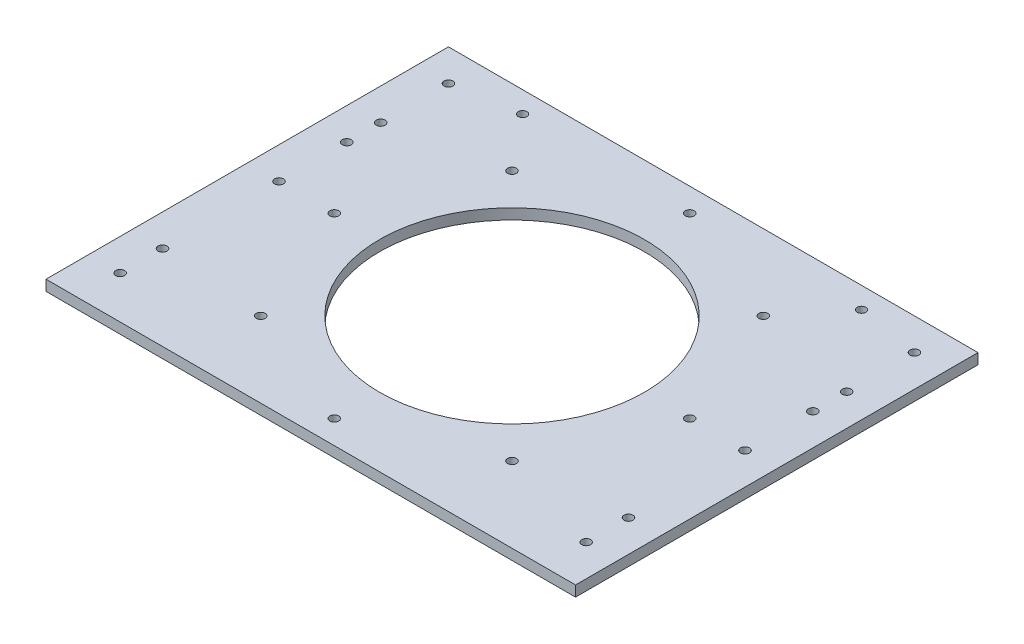
SolidWorks part; units mm, degrees
material "Thornel Mat VMA"
ref_plane "前视基准面" through (0, 0, 0) normal (0, 0, 1) x (1, 0, 0)
ref_plane "上视基准面" through (0, 0, 0) normal (0, 1, 0) x (1, 0, 0)
ref_plane "右视基准面" through (0, 0, 0) normal (1, 0, 0) x (0, 0, -1)
other "Configuration Table"
sketch "草图1" plane through (0, 0, 0) normal (0, 1, 0) x (1, 0, 0)
  line L1 (-125, 95) -> (125, 95)
  line L2 (-125, 95) -> (-125, -95)
  line L3 (-125, -95) -> (125, -95)
  line L4 (125, 95) -> (125, -95)
  line L5 (-125, 95) -> (125, -95) construction
  line L6 (-125, -95) -> (125, 95) construction
  point P0 (0, 0)
  dimension "D1" = 250
  dimension "D2" = 190
extrude "凸台-拉伸1" add sketch "草图1" along normal blind 5
sketch "草图2" plane through (0, 5, 0) normal (0, 1, 0) x (1, 0, 0)
  circle A0 centre (0, 0) radius 83.9 construction
  circle A1 centre (-83.9, 0) radius 2.1
  circle A2 centre (-59.3263, 59.3263) radius 2.1
  circle A3 centre (0, 83.9) radius 2.1
  circle A4 centre (59.3263, 59.3263) radius 2.1
  circle A5 centre (83.9, 0) radius 2.1
  circle A6 centre (59.3263, -59.3263) radius 2.1
  circle A7 centre (0, -83.9) radius 2.1
  circle A8 centre (-59.3263, -59.3263) radius 2.1
  point P22 (0, 0)
  dimension "D1" = 167.8
  dimension "D2" = 4.2
  dimension "D3" = 8
extrude "切除-拉伸1" cut sketch "草图2" against normal blind 10
sketch "草图3" plane through (0, 5, 0) normal (0, 1, 0) x (1, 0, 0)
  circle A0 centre (0, 0) radius 62.5
  dimension "D1" = 125
extrude "切除-拉伸2" cut sketch "草图3" against normal blind 10
sketch "草图4" plane through (0, 5, 0) normal (0, 1, 0) x (1, 0, 0)
  line L0 (125, 95) -> (-125, 95) construction
  line L1 (-125, 95) -> (-125, -95) construction
  line L2 (0, 95) -> (0, 86.5152) construction
  line L3 (-125, -95) -> (125, -95) construction
  line L5 (0, 0) -> (0, 21.5851) construction
  circle A1 centre (-110, 80) radius 2.1
  circle A2 centre (-110, 48) radius 2.1
  circle A3 centre (110, 48) radius 2.1
  circle A4 centre (110, 80) radius 2.1
  circle A5 centre (-110, -75) radius 2.1
  circle A6 centre (110, -75) radius 2.1
  circle A7 centre (-110, 32) radius 2.1
  circle A8 centre (-110, 0) radius 2.1
  circle A9 centre (110, 32) radius 2.1
  circle A10 centre (110, 0) radius 2.1
  circle A11 centre (-110, -55) radius 2.1
  circle A12 centre (110, -55) radius 2.1
  dimension "D1" = 4.2
  dimension "D6" = 20
  dimension "D7" = 16
  dimension "D8" = 32
  dimension "D9" = 4.2
  dimension "D11" = 4.2
  dimension "D2" = 32
  dimension "D3" = 15
  dimension "D4" = 15
  dimension "D5" = 20
  dimension "D10" = 220
extrude "切除-拉伸3" cut sketch "草图4" against normal up to next
sketch "草图5" plane through (0, 5, 0) normal (0, 1, 0) x (1, 0, 0)
  line L4 (125, -95) -> (125, 95)
  line L5 (125, 95) -> (-125, 95)
  line L6 (-125, 95) -> (-125, -95)
  line L7 (-125, -95) -> (125, -95)
  line L8 (125, -95) -> (125, 95)
  line L9 (125, 95) -> (-125, 95)
  line L10 (-125, 95) -> (-125, -95)
  line L11 (-125, -95) -> (125, -95)
  circle A0 centre (-80, 85) radius 2.05 construction
  circle A1 centre (80, 85) radius 2.05 construction
  circle A2 centre (-80, 85) radius 2.05
  circle A3 centre (80, 85) radius 2.05
  dimension "D1" = 0
extrude "切除-拉伸4" cut sketch "草图5" against normal blind 10 flip side to cut
